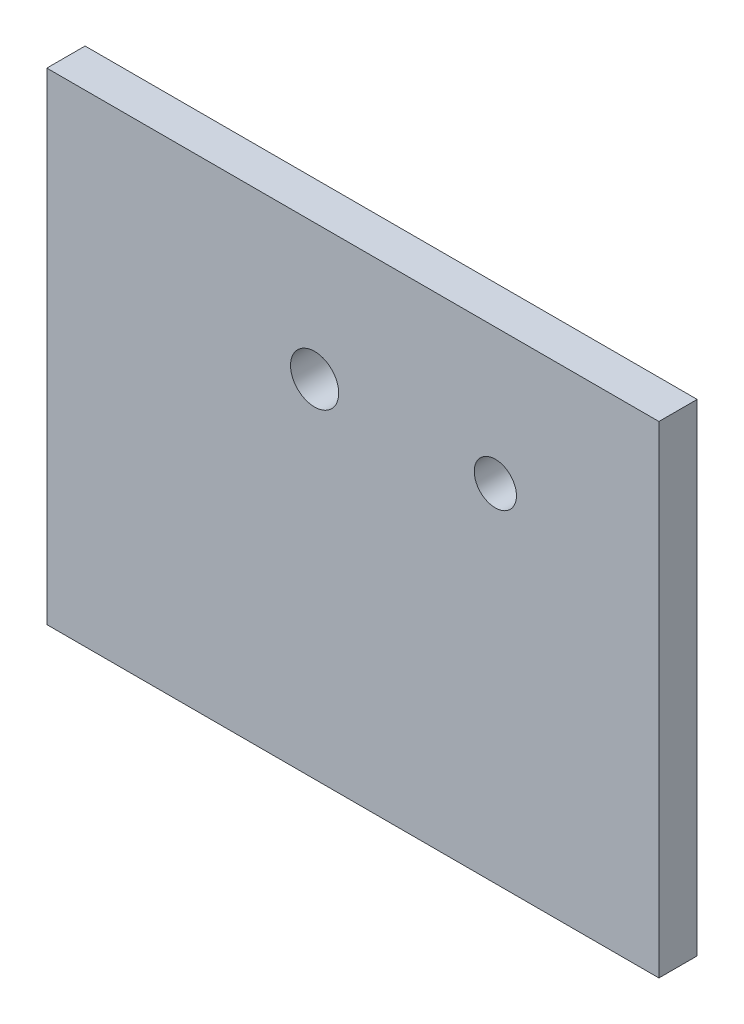
SolidWorks part; units mm, degrees
ref_plane "Front Plane" through (0, 0, 0) normal (0, 0, 1) x (1, 0, 0)
ref_plane "Top Plane" through (0, 0, 0) normal (0, 1, 0) x (1, 0, 0)
ref_plane "Right Plane" through (0, 0, 0) normal (1, 0, 0) x (0, 0, -1)
sketch "Sketch1" plane through (0, 0, 0) normal (0, 0, 1) x (1, 0, 0)
  line L1 (0, 0) -> (101.6, 0)
  line L2 (0, 0) -> (0, -80)
  line L3 (0, -80) -> (101.6, -80)
  line L4 (101.6, 0) -> (101.6, -80)
  circle A1 centre (44.45, -22.5) radius 4
  circle A2 centre (74.45, -22.5) radius 3.5
  dimension "D6" = 7
  dimension "D3" = 22.5
  dimension "D4" = 8
  dimension "D5" = 44.45
  dimension "D1" = 80
  dimension "D2" = 101.6
  dimension "D7" = 30
extrude "Boss-Extrude1" add sketch "Sketch1" along normal blind 6.35
